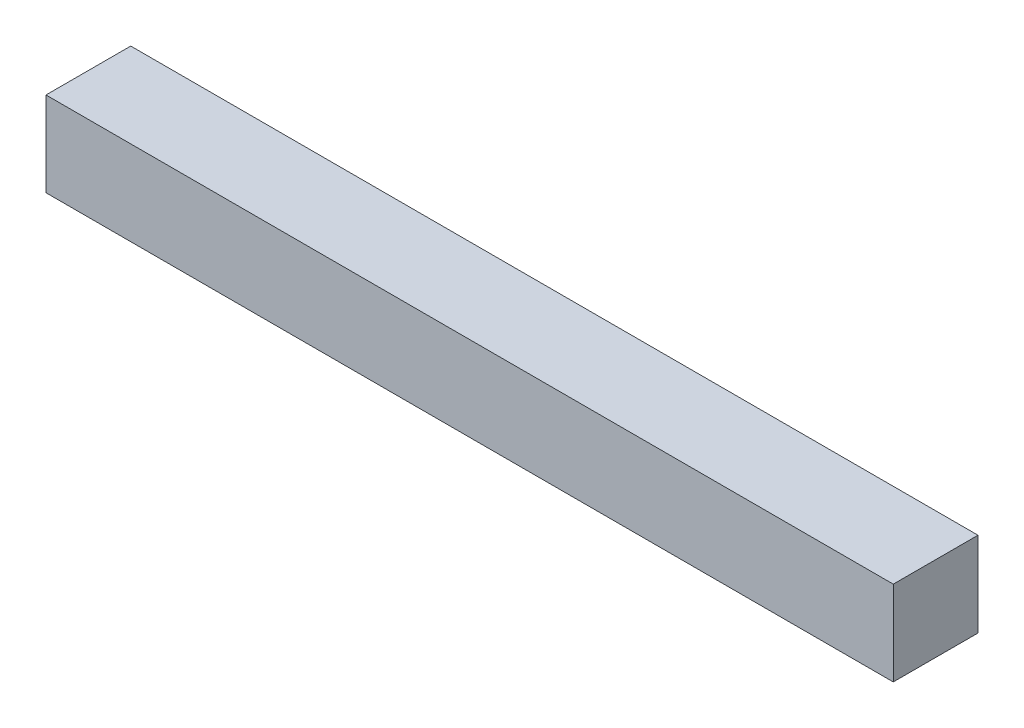
SolidWorks part; units mm, degrees
ref_plane "Front Plane" through (0, 0, 0) normal (0, 0, 1) x (1, 0, 0)
ref_plane "Top Plane" through (0, 0, 0) normal (0, 1, 0) x (1, 0, 0)
ref_plane "Right Plane" through (0, 0, 0) normal (1, 0, 0) x (0, 0, -1)
other "Configuration Table"
sketch "Sketch1" plane through (0, 0, 0) normal (0, 0, 1) x (1, 0, 0)
  line L1 (0, 0) -> (10, 0)
  line L2 (0, 0) -> (0, 1)
  line L3 (0, 1) -> (10, 1)
  line L4 (10, 0) -> (10, 1)
  dimension "D1" = 10
  dimension "D2" = 1
extrude "Extrude4" add sketch "Sketch1" along normal blind 1
